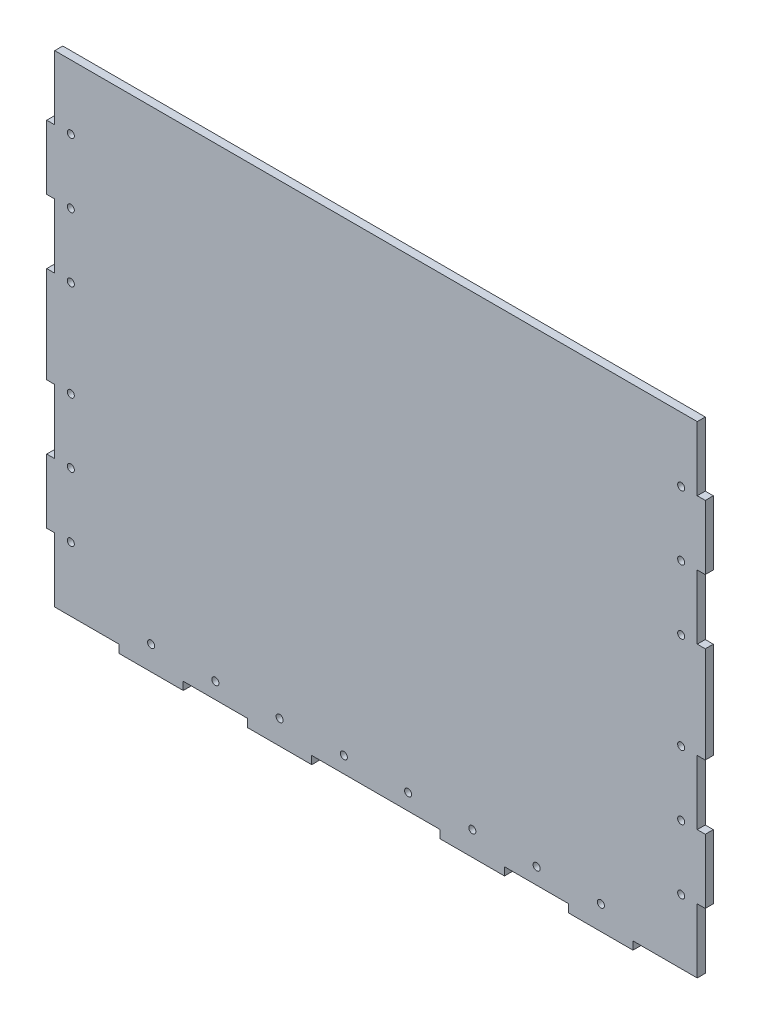
SolidWorks part; units mm, degrees
ref_plane "前视基准面" through (0, 0, 0) normal (0, 0, 1) x (1, 0, 0)
ref_plane "上视基准面" through (0, 0, 0) normal (0, 1, 0) x (1, 0, 0)
ref_plane "右视基准面" through (0, 0, 0) normal (1, 0, 0) x (0, 0, -1)
sketch "草图1" plane through (0, 0, 0) normal (0, 0, 1) x (1, 0, 0)
  line L2 (-200, 150) -> (200, 150)
  line L3 (200, -150) -> (200, -110)
  line L4 (-200, -150) -> (-200, -110)
  line L5 (-200, -150) -> (-160, -150)
  line L6 (-200, -150) -> (-160, -150)
  line L7 (-160, -150) -> (-160, -155)
  line L8 (-160, -155) -> (-120, -155)
  line L9 (-120, -155) -> (-120, -150)
  line L10 (-120, -150) -> (-80, -150)
  line L11 (-80, -150) -> (-80, -155)
  line L12 (-80, -155) -> (-40, -155)
  line L13 (-40, -155) -> (-40, -150)
  line L14 (-40, -150) -> (40, -150)
  line L15 (40, -150) -> (40, -155)
  line L16 (40, -155) -> (80, -155)
  line L17 (80, -155) -> (80, -150)
  line L18 (80, -150) -> (120, -150)
  line L19 (120, -150) -> (120, -155)
  line L20 (120, -155) -> (160, -155)
  line L21 (160, -155) -> (160, -150)
  line L22 (80, -150) -> (120, -150)
  line L23 (-120, -150) -> (-80, -150)
  line L24 (-40, -150) -> (40, -150)
  line L25 (160, -150) -> (200, -150)
  line L26 (-200, 110) -> (-200, 150)
  line L27 (-200, -70) -> (-200, -30)
  line L28 (-205, -30) -> (-205, 30)
  line L29 (-205, 30) -> (-200, 30)
  line L30 (-200, 30) -> (-200, 70)
  line L31 (-200, 70) -> (-205, 70)
  line L32 (-205, 70) -> (-205, 110)
  line L33 (-205, 110) -> (-200, 110)
  line L34 (-205, -30) -> (-200, -30)
  line L35 (-200, -70) -> (-205, -70)
  line L36 (-205, -70) -> (-205, -110)
  line L37 (-205, -110) -> (-200, -110)
  line L38 (-200, 30) -> (-200, 70)
  line L39 (200, 110) -> (200, 150)
  line L40 (205, -70) -> (205, -110)
  line L41 (205, -110) -> (200, -110)
  line L42 (200, -70) -> (205, -70)
  line L43 (205, -30) -> (200, -30)
  line L44 (205, -30) -> (205, 30)
  line L45 (205, 30) -> (200, 30)
  line L46 (200, 70) -> (205, 70)
  line L47 (205, 70) -> (205, 110)
  line L48 (205, 110) -> (200, 110)
  line L49 (200, 30) -> (200, 70)
  line L50 (200, -70) -> (200, -30)
  circle A0 centre (-140, -140) radius 2.2
  circle A1 centre (-100, -140) radius 2.2
  circle A2 centre (-60, -140) radius 2.2
  circle A3 centre (-20, -140) radius 2.2
  circle A4 centre (20, -140) radius 2.2
  circle A5 centre (60, -140) radius 2.2
  circle A6 centre (100, -140) radius 2.2
  circle A7 centre (140, -140) radius 2.2
  circle A8 centre (-190, 110) radius 2.2
  circle A9 centre (-190, 70) radius 2.2
  circle A10 centre (-190, 30) radius 2.2
  circle A11 centre (-190, -30) radius 2.2
  circle A12 centre (-190, -70) radius 2.2
  circle A13 centre (-190, -110) radius 2.2
  circle A14 centre (190, -110) radius 2.2
  circle A15 centre (190, -70) radius 2.2
  circle A16 centre (190, -30) radius 2.2
  circle A17 centre (190, 30) radius 2.2
  circle A18 centre (190, 70) radius 2.2
  circle A19 centre (190, 110) radius 2.2
extrude "凸台-拉伸1" add sketch "草图1" along normal blind 5 contours L42 L50 L43 L44 L45 L49 L46 L47 L48 L39 L2 L26 L33 L32 L31 L30 L29 L28 L34 L27 L35 L36 L37 L4 L5 L7 L8 L9 L10 L11 L12 L13 L14 L15 L16 L17 L18 L19 L20 L21 L25 L3 L41 L40 A18 A16 A14
